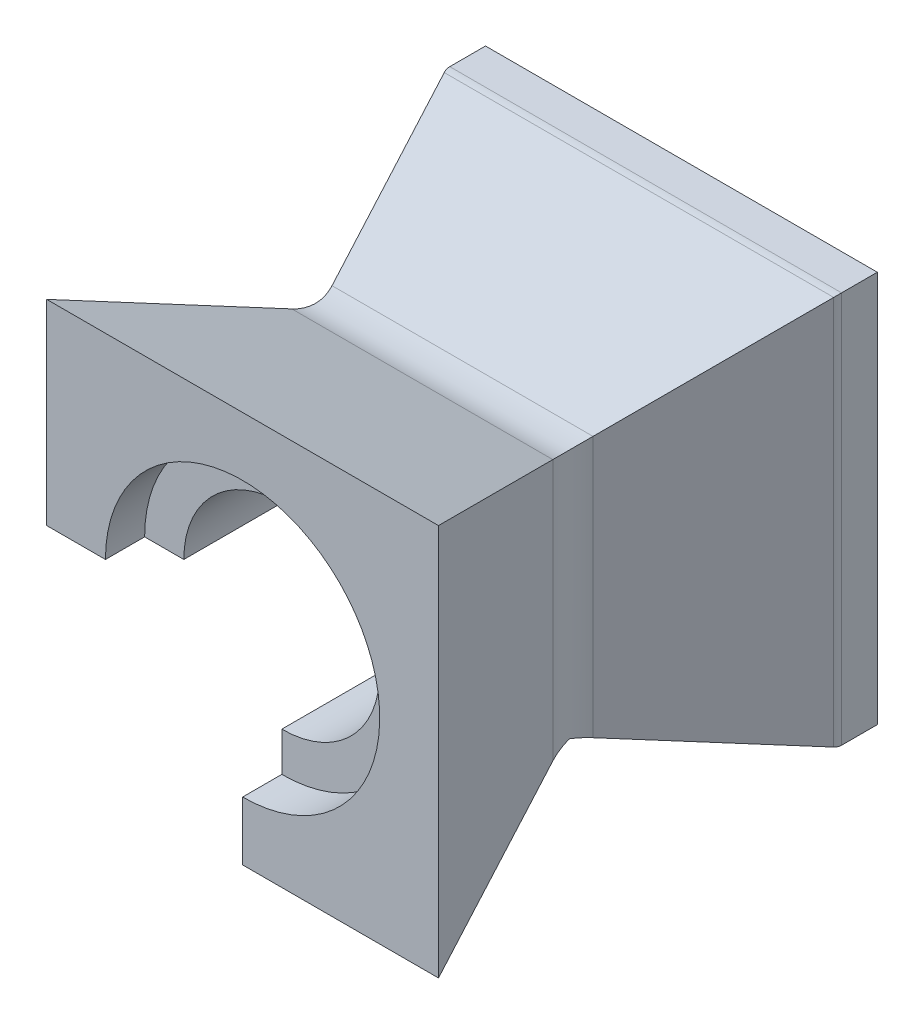
SolidWorks part; units mm, degrees
material "Acier inoxydable moulé"
ref_plane "Plan de face" through (0, 0, 0) normal (0, 0, 1) x (1, 0, 0)
ref_plane "Plan de dessus" through (0, 0, 0) normal (0, 1, 0) x (1, 0, 0)
ref_plane "Plan de droite" through (0, 0, 0) normal (1, 0, 0) x (0, 0, -1)
sketch "Esquisse2" plane through (0, 0, 0) normal (0, 0, 1) x (1, 0, 0)
  line L1 (-73.4104, 39.1618) -> (26.5896, 39.1618)
  line L2 (-73.4104, 39.1618) -> (-73.4104, -60.8382)
  line L3 (-73.4104, -60.8382) -> (26.5896, -60.8382)
  line L4 (26.5896, 39.1618) -> (26.5896, -60.8382)
  dimension "D1" = 100
  dimension "D2" = 100
extrude "Boss.-Extru.1" add sketch "Esquisse2" along normal blind 51 draft 20
mirror "Symétrie4" about plane through (0, 0, 51) normal (0, 0, 1) of "Boss.-Extru.1"
sketch "Esquisse3" plane through (0, 0, 102) normal (0, 0, 1) x (1, 0, 0)
  line L0 (26.5896, 39.1618) -> (-73.4104, -60.8382) construction
  line L1 (-73.4104, 39.1618) -> (26.5896, -60.8382) construction
  circle A0 centre (-23.4104, -10.8382) radius 25
  point P10 (-23.4104, -10.8382)
  point P11 (-23.4104, -10.8382)
  point P12 (-23.4104, -10.8382)
  point P13 (0, 0)
  dimension "D1" = 50
extrude "Enlèv. mat.-Extru.1" cut sketch "Esquisse3" against normal through all both and the other way through all
sketch "Esquisse5" plane through (0, 0, 102) normal (0, 0, 1) x (1, 0, 0)
  circle A0 centre (-23.4104, -10.8382) radius 35
  dimension "D1" = 70
extrude "Enlèv. mat.-Extru.2" cut sketch "Esquisse5" against normal blind 10 and the other way through all
sketch "Esquisse6" plane through (0, 0, 0) normal (0, 0, -1) x (-1, 0, 0)
  circle A1 centre (23.4104, -10.8382) radius 35
  circle A2 centre (23.4104, -10.8382) radius 35
  dimension "D1" = 0
extrude "Enlèv. mat.-Extru.3" cut sketch "Esquisse6" against normal blind 10
sketch "Esquisse7" plane through (0, 0, 0) normal (0, 0, -1) x (-1, 0, 0)
  line L0 (23.4104, -10.8382) -> (73.4104, -10.8382)
  line L1 (73.4104, 39.1618) -> (73.4104, -60.8382) construction
  line L2 (23.4104, -10.8382) -> (23.4104, -60.8382)
  line L3 (73.4104, -60.8382) -> (-26.5896, -60.8382) construction
  line L4 (23.4104, -60.8382) -> (73.4104, -60.8382)
  line L5 (73.4104, -60.8382) -> (73.4104, -10.8382)
extrude "Enlèv. mat.-Extru.4" cut sketch "Esquisse7" against normal through all
fillet "Congé1" radius 15 3 edges at (-54.8479, 4.8806, 51) (-23.4104, 20.5994, 51) (8.0271, -10.8382, 51)
sketch "Esquisse8" plane through (0, 0, 0) normal (0, 0, -1) x (-1, 0, 0)
  line L0 (23.4104, -10.8382) -> (-11.9449, 24.5172) construction
  line L1 (-26.5896, 39.1618) -> (-26.5896, -60.8382)
  line L2 (-11.9449, -46.1935) -> (58.7657, 24.5172) construction
  line L3 (-17.2482, 29.8205) -> (-6.6416, 19.2139) construction
  line L4 (-15.1269, 31.9418) -> (-4.5203, 21.3352)
  line L5 (-19.3696, 27.6992) -> (-8.763, 17.0926)
  line L6 (-4.5203, 17.0926) -> (-26.5896, 39.1618) construction
  line L7 (-17.2482, -51.4968) -> (-6.6416, -40.8902) construction
  line L12 (-19.3696, -49.3755) -> (-8.763, -38.7689)
  line L13 (-15.1269, -53.6181) -> (-4.5203, -43.0115)
  line L14 (53.4624, 19.2139) -> (64.069, 29.8205) construction
  line L15 (51.3411, 21.3352) -> (61.9477, 31.9418)
  line L16 (55.5838, 17.0926) -> (66.1904, 27.6992)
  line L17 (73.4104, -10.8382) -> (58.4104, -10.8382) construction
  line L18 (73.4104, 39.1618) -> (73.4104, -10.8382) construction
  line L19 (-26.5896, 39.1618) -> (73.4104, 39.1618) construction
  line L20 (-23.5896, 36.1618) -> (-23.5896, -57.8382)
  line L21 (23.4104, -60.8382) -> (-26.5896, -60.8382) construction
  line L22 (23.4104, -45.8382) -> (23.4104, -60.8382) construction
  line L23 (23.4104, -57.8382) -> (23.4104, -60.8382)
  line L24 (23.4104, -60.8382) -> (-26.5896, -60.8382)
  line L25 (-26.5896, 39.1618) -> (73.4104, 39.1618)
  line L26 (73.4104, 39.1618) -> (73.4104, -10.8382)
  line L27 (73.4104, -10.8382) -> (70.4104, -10.8382)
  line L29 (-26.5896, 36.1618) -> (73.4104, 36.1618)
  line L30 (-23.5896, 36.1618) -> (70.4104, 36.1618)
  line L32 (70.4104, 39.1618) -> (70.4104, -10.8382)
  line L33 (70.4104, 36.1618) -> (70.4104, -10.8382)
  line L35 (23.4104, -57.8382) -> (-26.5896, -57.8382)
  line L36 (23.4104, -57.8382) -> (-23.5896, -57.8382)
  circle A0 centre (23.4104, -10.8382) radius 50 construction
  arc A1 (-15.1269, 31.9418) -> (-19.3696, 27.6992) centre (-17.2482, 29.8205) ccw
  arc A2 (-8.763, 17.0926) -> (-4.5203, 21.3352) centre (-6.6416, 19.2139) ccw
  arc A7 (-19.3696, -49.3755) -> (-15.1269, -53.6181) centre (-17.2482, -51.4968) ccw
  arc A8 (-4.5203, -43.0115) -> (-8.763, -38.7689) centre (-6.6416, -40.8902) ccw
  arc A9 (51.3411, 21.3352) -> (55.5838, 17.0926) centre (53.4624, 19.2139) ccw
  arc A10 (66.1904, 27.6992) -> (61.9477, 31.9418) centre (64.069, 29.8205) ccw
  point P11 (-11.9449, 24.5172)
  point P18 (-11.9449, -46.1935)
  point P28 (58.7657, 24.5172)
  point P40 (-23.5896, 39.1618)
  point P41 (-23.5896, -60.8382)
  dimension "D1" = 15
  dimension "D2" = 3
  dimension "D3" = 3
  dimension "D4" = 15
  dimension "D5" = 15
  dimension "D6" = 3
  dimension "D7" = 3
  dimension "D8" = 3
extrude "Enlèv. mat.-Extru.8" cut sketch "Esquisse8" against normal blind 10 contours L5 A2 L4 A1 | L13 A8 L12 A7 | L15 A10 L16 A9
sketch "Esquisse9" plane through (0, 0, 0) normal (0, 0, -1) x (-1, 0, 0)
  line L2 (-4.5203, 21.3352) -> (-15.1269, 31.9418)
  line L3 (-19.3696, 27.6992) -> (-8.763, 17.0926)
  line L4 (-4.5203, 21.3352) -> (-15.1269, 31.9418)
  line L5 (-19.3696, 27.6992) -> (-8.763, 17.0926)
  line L6 (-8.763, -38.7689) -> (-19.3696, -49.3755)
  line L7 (-15.1269, -53.6181) -> (-4.5203, -43.0115)
  line L8 (-8.763, -38.7689) -> (-19.3696, -49.3755)
  line L9 (-15.1269, -53.6181) -> (-4.5203, -43.0115)
  line L10 (61.9477, 31.9418) -> (51.3411, 21.3352)
  line L11 (55.5838, 17.0926) -> (66.1904, 27.6992)
  line L12 (61.9477, 31.9418) -> (51.3411, 21.3352)
  line L13 (55.5838, 17.0926) -> (66.1904, 27.6992)
  line L22 (-26.5896, -60.8382) -> (23.4104, -60.8382)
  line L23 (-26.5896, 39.1618) -> (-26.5896, -60.8382)
  line L24 (73.4104, 39.1618) -> (-26.5896, 39.1618)
  line L25 (73.4104, -10.8382) -> (73.4104, 39.1618)
  line L26 (70.4104, -10.8382) -> (73.4104, -10.8382)
  line L27 (70.4104, 36.1618) -> (70.4104, -10.8382)
  line L28 (-23.5896, 36.1618) -> (70.4104, 36.1618)
  line L29 (-23.5896, -57.8382) -> (-23.5896, 36.1618)
  line L30 (23.4104, -57.8382) -> (-23.5896, -57.8382)
  line L31 (23.4104, -60.8382) -> (23.4104, -57.8382)
  line L32 (-26.5896, -60.8382) -> (23.4104, -60.8382)
  line L33 (-26.5896, 39.1618) -> (-26.5896, -60.8382)
  line L34 (73.4104, 39.1618) -> (-26.5896, 39.1618)
  line L35 (73.4104, -10.8382) -> (73.4104, 39.1618)
  line L36 (70.4104, -10.8382) -> (73.4104, -10.8382)
  line L37 (70.4104, 36.1618) -> (70.4104, -10.8382)
  line L38 (-23.5896, 36.1618) -> (70.4104, 36.1618)
  line L39 (-23.5896, -57.8382) -> (-23.5896, 36.1618)
  line L40 (23.4104, -57.8382) -> (-23.5896, -57.8382)
  line L41 (23.4104, -60.8382) -> (23.4104, -57.8382)
  arc A2 (-8.763, 17.0926) -> (-4.5203, 21.3352) centre (-6.6416, 19.2139) ccw
  arc A3 (-15.1269, 31.9418) -> (-19.3696, 27.6992) centre (-17.2482, 29.8205) ccw
  arc A4 (-8.763, 17.0926) -> (-4.5203, 21.3352) centre (-6.6416, 19.2139) ccw
  arc A5 (-15.1269, 31.9418) -> (-19.3696, 27.6992) centre (-17.2482, 29.8205) ccw
  arc A6 (-4.5203, -43.0115) -> (-8.763, -38.7689) centre (-6.6416, -40.8902) ccw
  arc A7 (-19.3696, -49.3755) -> (-15.1269, -53.6181) centre (-17.2482, -51.4968) ccw
  arc A8 (-4.5203, -43.0115) -> (-8.763, -38.7689) centre (-6.6416, -40.8902) ccw
  arc A9 (-19.3696, -49.3755) -> (-15.1269, -53.6181) centre (-17.2482, -51.4968) ccw
  arc A10 (66.1904, 27.6992) -> (61.9477, 31.9418) centre (64.069, 29.8205) ccw
  arc A11 (51.3411, 21.3352) -> (55.5838, 17.0926) centre (53.4624, 19.2139) ccw
  arc A12 (66.1904, 27.6992) -> (61.9477, 31.9418) centre (64.069, 29.8205) ccw
  arc A13 (51.3411, 21.3352) -> (55.5838, 17.0926) centre (53.4624, 19.2139) ccw
  dimension "D1" = 0
  dimension "D2" = 0
  dimension "D3" = 0
  dimension "D4" = 0
extrude "Boss.-Extru.2" add sketch "Esquisse9" along normal blind 10 contours L32 L41 L40 L39 L38 L37 L36 L35 L34 L33
fillet "Congé2" radius 5 4 edges at (-73.4104, 14.1618, 0) (-23.4104, 39.1618, 0) (26.5896, -10.8382, 0) (1.5896, -60.8382, 0)
equation "\"A\"= 102"
equation "\"B\"= 100"
equation "\"C\"= 20"
equation "\"D1@Esquisse2\"=\"B\""
equation "\"D2@Esquisse2\"=\"B\""
equation "\"D3@Boss.-Extru.1\"=\"C\""
equation "\"D1@Boss.-Extru.1\"=\"A\"/2"
